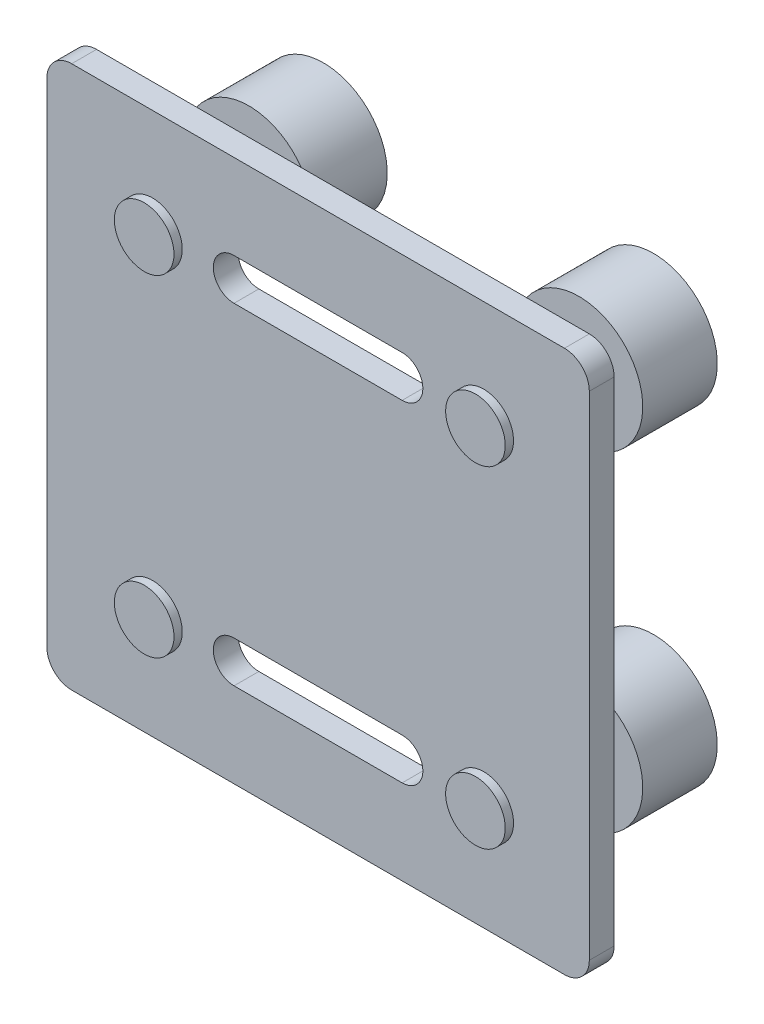
SolidWorks part; units mm, degrees
other "标注1"
sketch "草图5" plane through (-32.75, 32.75, 6) normal (-0.0636, 0.9944, 0.0841) x (-0.9921, -0.0721, 0.103)
ref_plane "前视基准面" through (0, 0, 0) normal (0, 0, 1) x (1, 0, 0)
ref_plane "上视基准面" through (0, 0, 0) normal (0, 1, 0) x (1, 0, 0)
ref_plane "右视基准面" through (0, 0, 0) normal (1, 0, 0) x (0, 0, -1)
sketch "草图1" plane through (0, 0, 0) normal (0, 0, 1) x (1, 0, 0)
  line L0 (-32.75, 20) -> (40.0364, 20) construction
  line L1 (32.75, -32.75) -> (-32.75, -32.75)
  line L2 (32.75, -32.75) -> (32.75, 32.75)
  line L3 (32.75, 32.75) -> (-32.75, 32.75)
  line L4 (-32.75, -32.75) -> (-32.75, 32.75)
  line L5 (32.75, -32.75) -> (-32.75, 32.75) construction
  line L6 (32.75, 32.75) -> (-32.75, -32.75) construction
  line L7 (-20, 32.75) -> (-20, 20) construction
  line L8 (0, 0) -> (0, 37.1413) construction
  line L9 (-10.15, 32.75) -> (-10.15, 20) construction
  line L10 (-10.15, 22.5) -> (10.15, 22.5)
  line L11 (-10.15, 17.5) -> (10.15, 17.5)
  line L12 (0, 0) -> (27.1673, 0) construction
  line L13 (-10.15, -22.5) -> (10.15, -22.5)
  line L14 (-10.15, -17.5) -> (10.15, -17.5)
  circle A2 centre (-20, 20) radius 3.6
  circle A3 centre (20, 20) radius 3.6
  arc A5 (-10.15, 22.5) -> (-10.15, 17.5) centre (-10.15, 20) ccw
  arc A6 (10.15, 22.5) -> (10.15, 17.5) centre (10.15, 20) cw
  circle A7 centre (20, -20) radius 3.6
  arc A8 (10.15, -22.5) -> (10.15, -17.5) centre (10.15, -20) ccw
  arc A9 (-10.15, -22.5) -> (-10.15, -17.5) centre (-10.15, -20) cw
  circle A10 centre (-20, -20) radius 3.6
  point P0 (0, 0)
  point P25 (0, 17.5)
  point P27 (0, 22.5)
  dimension "D1" = 65.5
  dimension "D5" = 7.2
  dimension "D2" = 65.5
  dimension "D3" = 12.75
  dimension "D4" = 12.75
extrude "凸台-拉伸1" add sketch "草图1" along normal blind 3
fillet "圆角1" radius 3 4 edges at (-32.75, -32.75, 1.5) (32.75, -32.75, 1.5) (32.75, 32.75, 1.5) (-32.75, 32.75, 1.5)
sketch "草图3" plane through (0, 0, 3) normal (0, 0, 1) x (1, 0, 0)
  circle A0 centre (-20, 20) radius 3.6
  circle A1 centre (-20, -20) radius 3.6
  circle A2 centre (20, 20) radius 3.6
  circle A3 centre (20, -20) radius 3.6
extrude "凸台-拉伸2" add sketch "草图3" against normal blind 11.5 and the other way blind 1
sketch "草图4" plane through (0, 0, -8.5) normal (0, 0, -1) x (-1, 0, 0)
  circle A0 centre (-20, -20) radius 7.7
  circle A1 centre (-20, 19.85) radius 7.7
  circle A2 centre (19.85, 19.85) radius 7.7
  circle A3 centre (19.85, -20) radius 7.7
  point P12 (-0.075, -0.075)
  dimension "D1" = 4
  dimension "D2" = 15.4
extrude "凸台-拉伸3" add sketch "草图4" along normal blind 9
